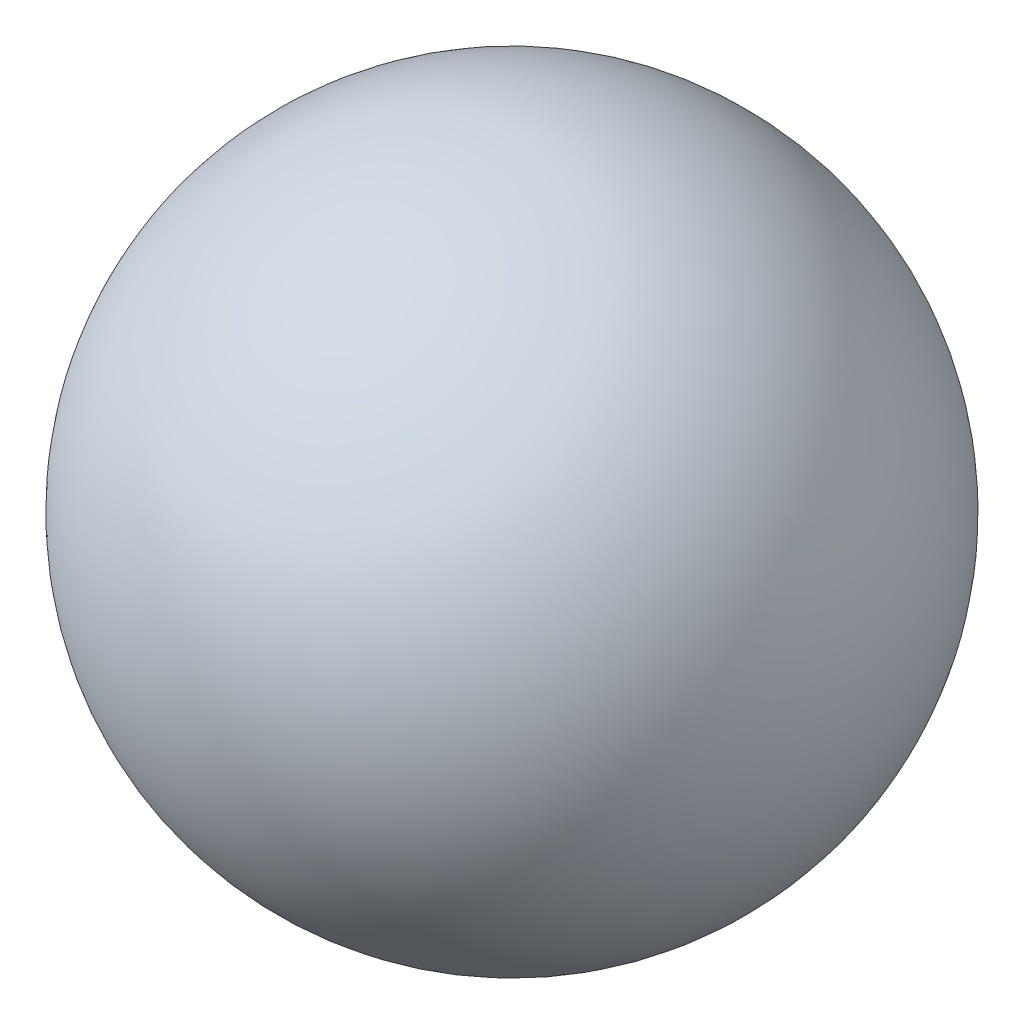
SolidWorks part; units mm, degrees
ref_plane "Front Plane" through (0, 0, 0) normal (0, 0, 1) x (1, 0, 0)
ref_plane "Top Plane" through (0, 0, 0) normal (0, 1, 0) x (1, 0, 0)
ref_plane "Right Plane" through (0, 0, 0) normal (1, 0, 0) x (0, 0, -1)
sketch "Sketch1" plane through (0, 0, 0) normal (0, 0, 1) x (1, 0, 0)
  line L0 (-1.2446, 0) -> (1.2446, 0) construction
  point P4 (0, 0)
  dimension "Diameter" = 2.4892
sketch "Sketch3" plane through (0, 0, 0) normal (0, 0, 1) x (1, 0, 0)
  line L0 (-1.2446, 0) -> (1.2446, 0)
  arc A1 (1.2446, 0) -> (-1.2446, 0) centre (0, 0) ccw
revolve "Revolve1" add sketch "Sketch3" angle 360 about L0
